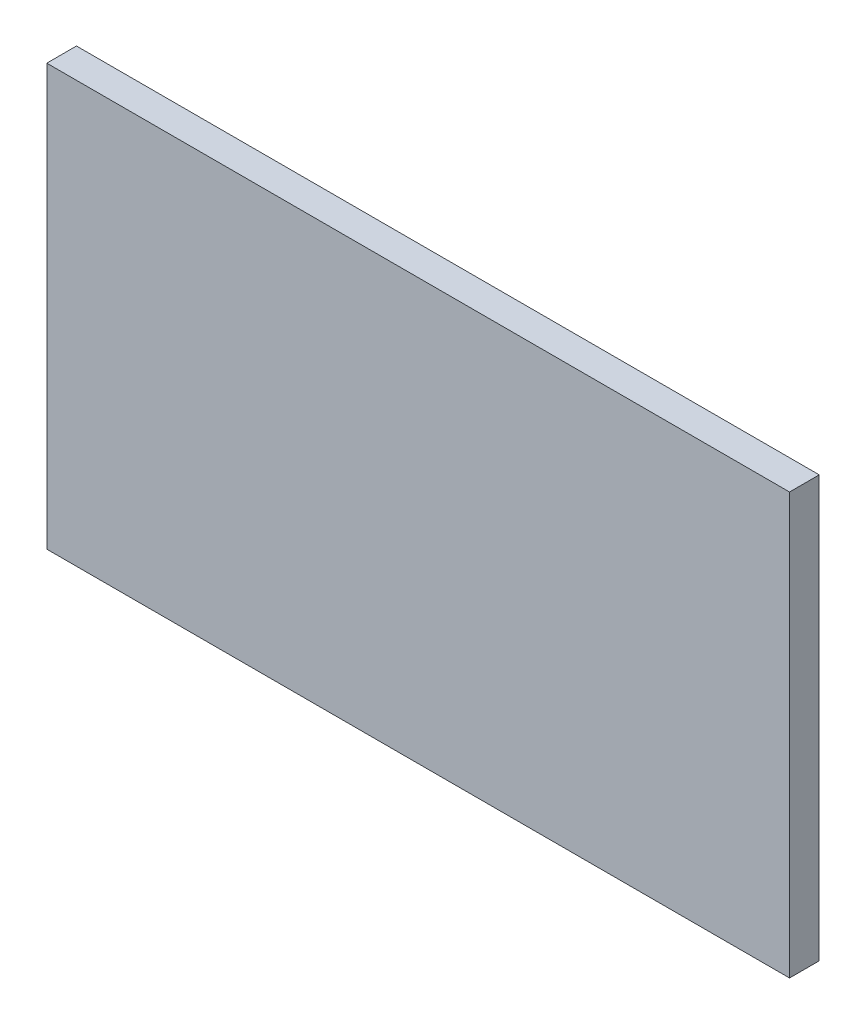
SolidWorks part; units mm, degrees
ref_plane "前视基准面" through (0, 0, 0) normal (0, 0, 1) x (1, 0, 0)
ref_plane "上视基准面" through (0, 0, 0) normal (0, 1, 0) x (1, 0, 0)
ref_plane "右视基准面" through (0, 0, 0) normal (1, 0, 0) x (0, 0, -1)
other "Configuration Table"
sketch "草图1" plane through (0, 0, 0) normal (0, 0, 1) x (1, 0, 0)
  line L1 (-750, -425) -> (750, -425)
  line L2 (-750, -425) -> (-750, 425)
  line L3 (-750, 425) -> (750, 425)
  line L4 (750, -425) -> (750, 425)
  line L5 (-750, -425) -> (750, 425) construction
  line L6 (-750, 425) -> (750, -425) construction
  point P0 (0, 0)
extrude "凸台-拉伸1" add sketch "草图1" along normal blind 60
